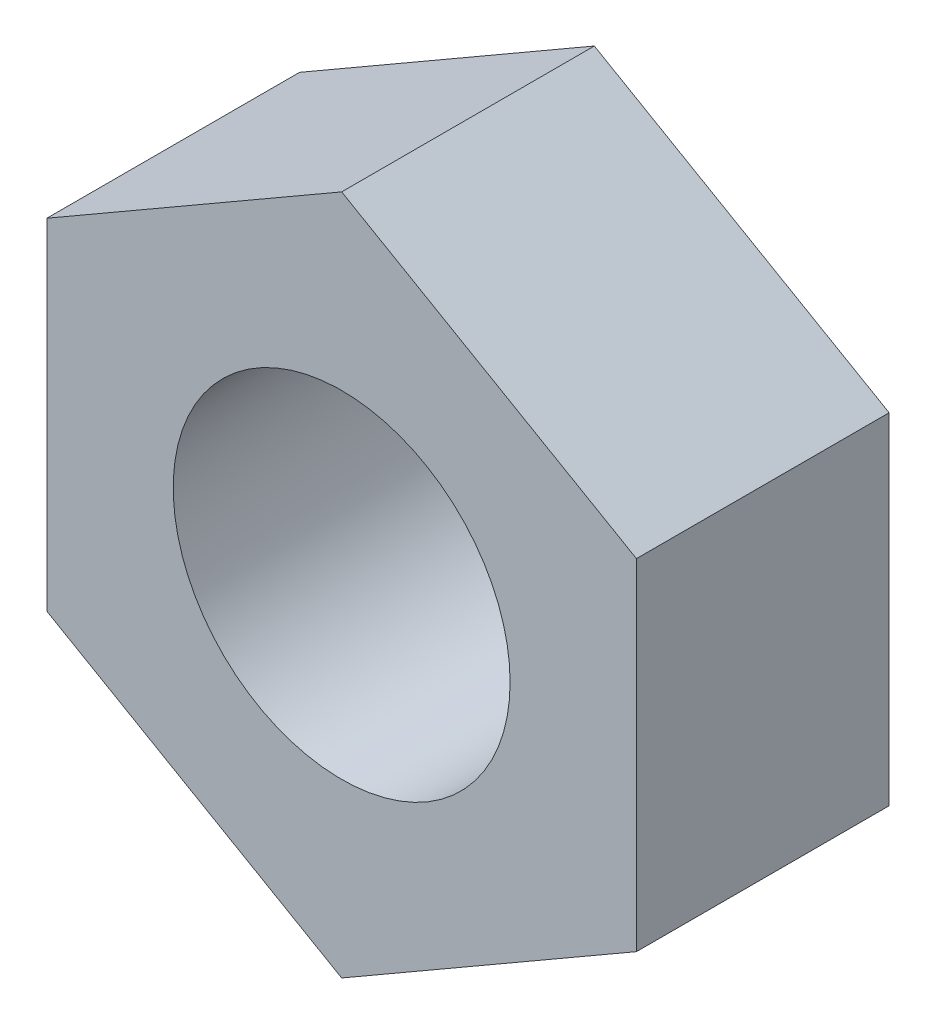
SolidWorks part; units mm, degrees
ref_plane "Спереди" through (0, 0, 0) normal (0, 0, 1) x (1, 0, 0)
ref_plane "Сверху" through (0, 0, 0) normal (0, 1, 0) x (1, 0, 0)
ref_plane "Справа" through (0, 0, 0) normal (1, 0, 0) x (0, 0, -1)
sketch "Sketch1" plane through (0, 0, 0) normal (0, 0, 1) x (1, 0, 0)
  line L1 (0, 4.0415) -> (-3.5, 2.0207)
  line L2 (-3.5, 2.0207) -> (-3.5, -2.0207)
  line L3 (-3.5, -2.0207) -> (0, -4.0415)
  line L4 (0, -4.0415) -> (3.5, -2.0207)
  line L5 (3.5, -2.0207) -> (3.5, 2.0207)
  line L6 (3.5, 2.0207) -> (0, 4.0415)
  circle A0 centre (0, 0) radius 3.5 construction
  circle A1 centre (0, 0) radius 2
  dimension "D1" = 7
  dimension "D2" = 4
extrude "Boss-Extrude1" add sketch "Sketch1" along normal blind 3
